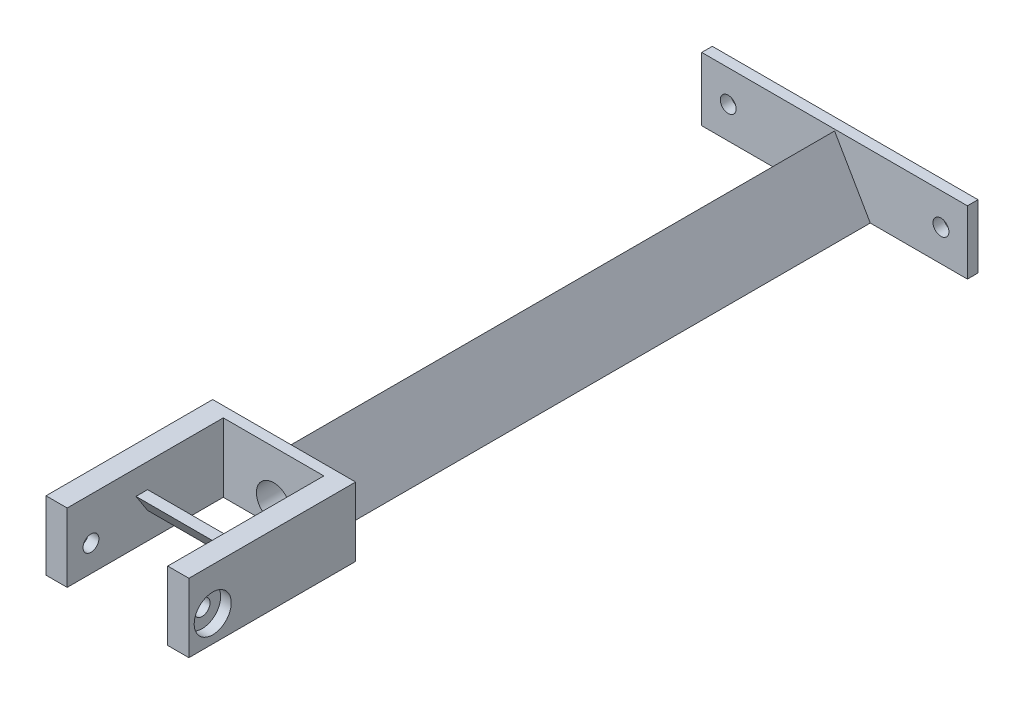
SolidWorks part; units mm, degrees
ref_plane "前视基准面" through (0, 0, 0) normal (0, 0, 1) x (1, 0, 0)
ref_plane "上视基准面" through (0, 0, 0) normal (0, 1, 0) x (1, 0, 0)
ref_plane "右视基准面" through (0, 0, 0) normal (1, 0, 0) x (0, 0, -1)
other "Configuration Table"
sketch "草图1" plane through (0, 0, 0) normal (0, 0, 1) x (1, 0, 0)
  line L1 (-25.1, 6) -> (25.1, 6)
  line L2 (-25.1, 6) -> (-25.1, -16)
  line L3 (-25.1, -16) -> (25.1, -16)
  line L4 (25.1, 6) -> (25.1, -16)
  point P0 (0, 0)
  dimension "D1" = 22
  dimension "D2" = 6
  dimension "50.2" = 50.2
extrude "凸台-拉伸1" add sketch "草图1" along normal blind 2.5
sketch "草图2" plane through (0, 0, 2.5) normal (0, 0, 1) x (1, 0, 0)
  line L0 (0, -17.6) -> (0, 17.6) construction
  line L4 (-25.1, 0) -> (-15.1, 0) construction
  line L6 (25.1, 6) -> (-25.1, 6) construction
  line L7 (-25.1, 6) -> (-25.1, -16) construction
  circle A0 centre (-20.1, 0) radius 1.5
  circle A1 centre (20.1, 0) radius 1.5
  dimension "D2" = 3
  dimension "D1" = 6
  dimension "D3" = 5
extrude "切除-拉伸1" cut sketch "草图2" against normal blind 2.5
sketch "草图4" plane through (0, 0, 2.5) normal (0, 0, 1) x (1, 0, 0)
  line L0 (0, 6) -> (0, -16) construction
  line L1 (25.1, 6) -> (-25.1, 6) construction
  line L2 (-25.1, -16) -> (25.1, -16) construction
  line L3 (-13.5, -7) -> (-13.5, -23)
  line L4 (-13.5, -23) -> (-9.5, -23)
  line L5 (-9.5, -23) -> (-9.5, -7)
  line L6 (-9.5, -7) -> (-13.5, -7)
  line L7 (9.5, -7) -> (13.5, -7)
  line L8 (9.5, -23) -> (9.5, -7)
  line L9 (13.5, -23) -> (9.5, -23)
  line L10 (13.5, -7) -> (13.5, -23)
  dimension "D1" = 9.5
  dimension "D2" = 4
  dimension "D3" = 16
  dimension "7" = 7
extrude "凸台-拉伸2" add sketch "草图4" along normal blind 87 contours L6 L3 L4 L5 | L7 L10 L9 L8
sketch "草图5" plane through (9.5, 0, 0) normal (-1, 0, 0) x (0, 0, 1)
  line L0 (46, -7) -> (46, -23) construction
  line L1 (89.5, -7) -> (2.5, -7) construction
  line L2 (89.5, -23) -> (2.5, -23) construction
  circle A0 centre (46, -15) radius 2
extrude "凸台-拉伸3" add sketch "草图5" along normal up to next
sketch "草图6" plane through (-9.5, 0, 0) normal (1, 0, 0) x (0, 0, -1)
  line L0 (0, -16) -> (0, 6) construction
  line L1 (-2.5, 6) -> (0, 6) construction
  circle A0 centre (-85, -15) radius 1.5
  dimension "D2" = 3
  dimension "D1" = 85
  dimension "21" = 21
extrude "切除-拉伸2" cut sketch "草图6" along normal through all both and the other way through all
sketch "草图7" plane through (-13.5, 0, 0) normal (-1, 0, 0) x (0, 0, 1)
  circle A0 centre (85, -15) radius 3.5
extrude "切除-拉伸3" cut sketch "草图7" against normal blind 2
mirror "镜向1" about plane through (0, 0, 0) normal (1, 0, 0) of "切除-拉伸3"
fillet "圆角1" radius 2 2 edges at (11.5, -16, 2.5) (-11.5, -16, 2.5)
sketch "草图8" plane through (0, 6, 0) normal (0, 1, 0) x (1, 0, 0)
  line L0 (25.1, -2.5) -> (25.1, 0) construction
  line L1 (-25.1, -2.5) -> (25.1, -2.5)
  line L2 (-25.1, -2.5) -> (-25.1, 0)
  line L3 (-25.1, 0) -> (25.1, 0)
  line L4 (25.1, -2.5) -> (25.1, 0)
extrude "凸台-拉伸4" add sketch "草图8" along normal blind 3
sketch "草图9" plane through (0, 0, 0) normal (0, 0, -1) x (-1, 0, 0)
  line L1 (-25.1, 9) -> (-15.1, 9)
  line L2 (-25.1, 9) -> (-25.1, 6)
  line L3 (-25.1, 6) -> (-15.1, 6)
  line L4 (-15.1, 9) -> (-15.1, 6)
  dimension "D1" = 3
  dimension "D2" = 10
sketch "草图15" plane through (9.5, 0, 0) normal (-1, 0, 0) x (0, 0, 1)
  line L0 (74.3, -11.6) -> (76.5, -11.6)
  line L1 (76.5, -11.6) -> (74.3, -15)
  line L2 (74.3, -15) -> (74.3, -11.6)
  line L3 (89.5, -7) -> (2.5, -7) construction
  line L4 (89.5, -7) -> (89.5, -23) construction
  dimension "D1" = 2.2
  dimension "D2" = 3.4
  dimension "D3" = 4.6
  dimension "D4" = 13
extrude "凸台-拉伸8" add sketch "草图15" along normal blind 22
sketch "草图16" plane through (0, 0, 0) normal (0, 0, -1) x (-1, 0, 0)
  line L1 (-25.1, 9) -> (26.0254, 9)
  line L2 (-25.1, 9) -> (-25.1, -24.3988)
  line L3 (-25.1, -24.3988) -> (26.0254, -24.3988)
  line L4 (26.0254, 9) -> (26.0254, -24.3988)
extrude "切除-拉伸4" cut sketch "草图16" against normal blind 60
sketch "草图17" plane through (0, 0, 60) normal (0, 0, -1) x (-1, 0, 0)
  line L0 (9.5, -23) -> (13.5, -23) construction
  line L1 (-13.5, -7) -> (13.5, -7)
  line L2 (-13.5, -7) -> (-13.5, -23)
  line L3 (-13.5, -23) -> (13.5, -23)
  line L4 (13.5, -7) -> (13.5, -23)
  line L5 (13.5, -23) -> (13.5, -7) construction
extrude "凸台-拉伸9" add sketch "草图17" along normal blind 2
sketch "草图18" plane through (0, 0, 58) normal (0, 0, -1) x (-1, 0, 0)
  line L0 (-13.5, -23) -> (13.5, -23) construction
  line L1 (-13.5, -7) -> (-13.5, -23) construction
  line L5 (0, -8.3087) -> (-6.75, -20)
  line L6 (6.75, -20) -> (0, -8.3087)
  line L7 (-6.75, -20) -> (6.75, -20)
  dimension "D1" = 13.5
  dimension "D2" = 13.5
  dimension "D3" = 13.5
  dimension "D4" = 3
  dimension "D5" = 13.5
extrude "凸台-拉伸11" add sketch "草图18" along normal blind 104
sketch "草图19" plane through (0, 0, -46) normal (0, 0, -1) x (-1, 0, 0)
  line L0 (-13.5, -7) -> (-13.5, -23) construction
  line L1 (-25.1, -23) -> (25.1, -23)
  line L2 (-25.1, -23) -> (-25.1, 6)
  line L3 (-25.1, 6) -> (25.1, 6)
  line L4 (25.1, -23) -> (25.1, 6)
  line L5 (13.5, -23) -> (13.5, -7) construction
  line L6 (13.5, -7) -> (-13.5, -7) construction
  dimension "D1" = 11.6
  dimension "D2" = 11.6
  dimension "D3" = 13
extrude "凸台-拉伸12" add sketch "草图19" along normal blind 2
sketch "草图20" plane through (0, 0, -46) normal (0, 0, 1) x (1, 0, 0)
  line L0 (9.5, -7) -> (13.5, -7) construction
  line L1 (-9.5, -7) -> (-13.5, -7) construction
  line L2 (-13.5, -7) -> (-13.5, -23) construction
  line L3 (13.5, -7) -> (13.5, -23) construction
  circle A0 centre (-20.1, 0) radius 1.5
  circle A1 centre (20.1, 0) radius 1.5
  dimension "D1" = 3
  dimension "D2" = 3
  dimension "D3" = 7
  dimension "D4" = 7
  dimension "D5" = 6.6
  dimension "D6" = 6.6
extrude "切除-拉伸5" cut sketch "草图20" against normal blind 8
sketch "草图21" plane through (0, 0, -46) normal (0, 0, 1) x (1, 0, 0)
  line L0 (25.1, 6) -> (25.1, -23) construction
  line L9 (25.1, -6) -> (-25.1, -6)
  line L10 (25.1, -6) -> (25.1, -23)
  line L11 (25.1, -23) -> (-25.1, -23)
  line L12 (-25.1, -6) -> (-25.1, -23)
  circle A0 centre (-20.1, 0) radius 1.5 construction
  dimension "D1" = 6
sketch "草图22" plane through (25.1, 0, 0) normal (1, 0, 0) x (0, 0, -1)
  line L0 (46, -8) -> (46, -23)
  line L1 (46, -23) -> (46, -8) construction
  line L2 (46, -23) -> (46, -8) construction
split "分割1" trim tools "草图22" bodies to split 127 resulting bodies 128 129
move or copy body "实体-移动/复制1" bodies to move or copy 128 copy yes number of copies 1 translate (0, 14, 0) parameters "D1"=0, "D2"=14, "D3"=0
extrude "切除-拉伸7" cut sketch "草图21" against normal blind 164 and the other way blind 164
sketch "草图26" plane through (0, 0, -48) normal (0, 0, -1) x (-1, 0, 0)
  line L0 (25.1, -6) -> (-25.1, -6) construction
  circle A0 centre (0, -2.1) radius 3.25
  dimension "D2" = 6.5
  dimension "D1" = 3.9
extrude "切除-拉伸9" cut sketch "草图26" against normal blind 110 and the other way blind 10
